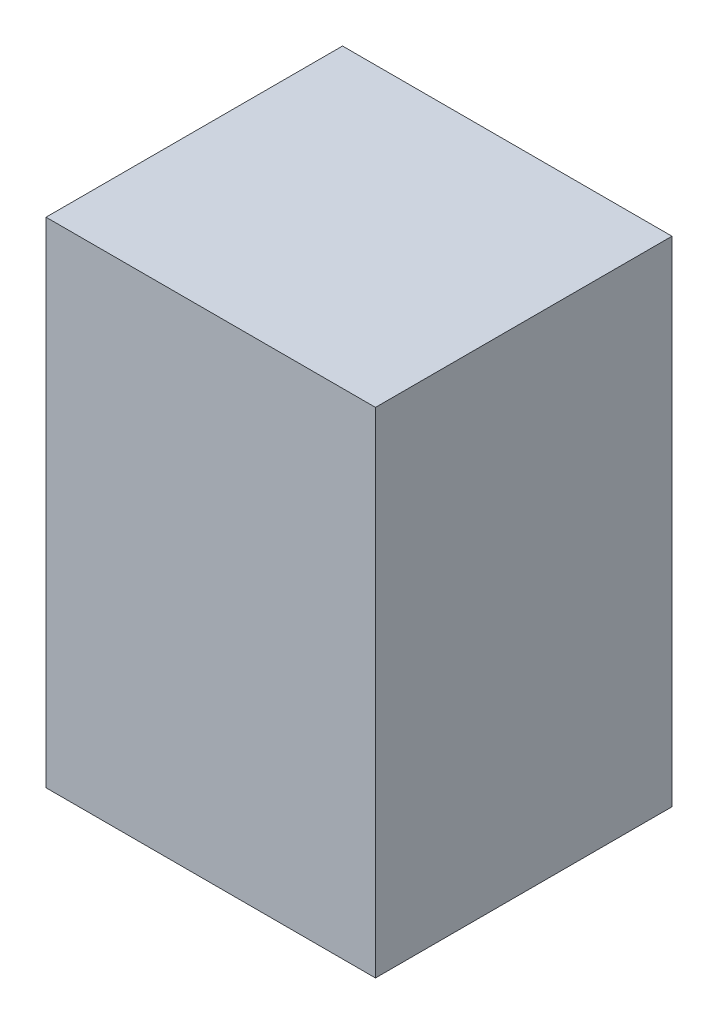
SolidWorks part; units mm, degrees
ref_plane "Front Plane" through (0, 0, 0) normal (0, 0, 1) x (1, 0, 0)
ref_plane "Top Plane" through (0, 0, 0) normal (0, 1, 0) x (1, 0, 0)
ref_plane "Right Plane" through (0, 0, 0) normal (1, 0, 0) x (0, 0, -1)
sketch "Sketch1" plane through (0, 0, 0) normal (0, 1, 0) x (1, 0, 0)
  line L1 (-100, 90) -> (100, 90)
  line L2 (-100, 90) -> (-100, -90)
  line L3 (-100, -90) -> (100, -90)
  line L4 (100, 90) -> (100, -90)
  line L5 (-100, 90) -> (100, -90) construction
  line L6 (-100, -90) -> (100, 90) construction
  point P0 (0, 0)
  dimension "D1" = 200
  dimension "D2" = 180
extrude "Boss-Extrude1" add sketch "Sketch1" along normal blind 300
